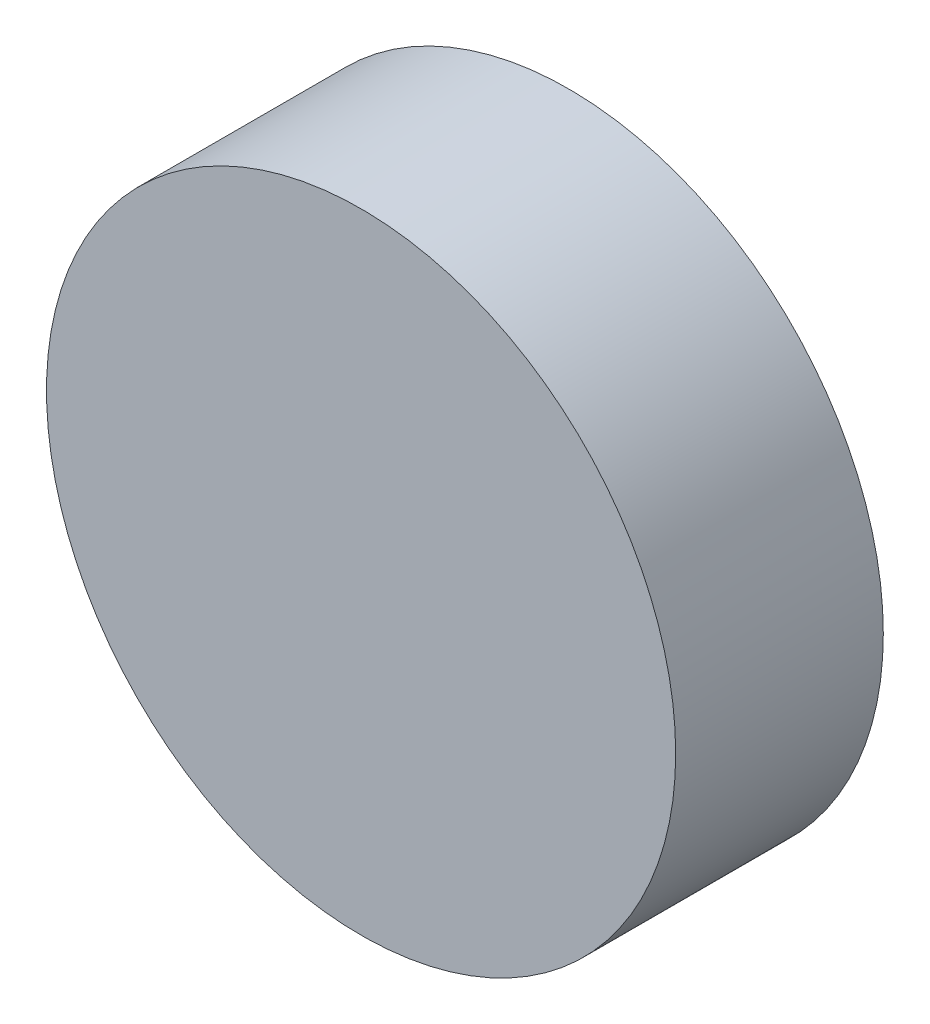
SolidWorks part; units mm, degrees
ref_plane "正面" through (0, 0, 0) normal (0, 0, 1) x (1, 0, 0)
ref_plane "平面" through (0, 0, 0) normal (0, 1, 0) x (1, 0, 0)
ref_plane "右側面" through (0, 0, 0) normal (1, 0, 0) x (0, 0, -1)
sketch "ｽｹｯﾁ1" plane through (0, 0, 0) normal (0, 0, 1) x (1, 0, 0)
  circle A0 centre (0, 0) radius 5
  dimension "D1" = 10
extrude "ﾎﾞｽ - 押し出し1" add sketch "ｽｹｯﾁ1" along normal mid plane 3.3
